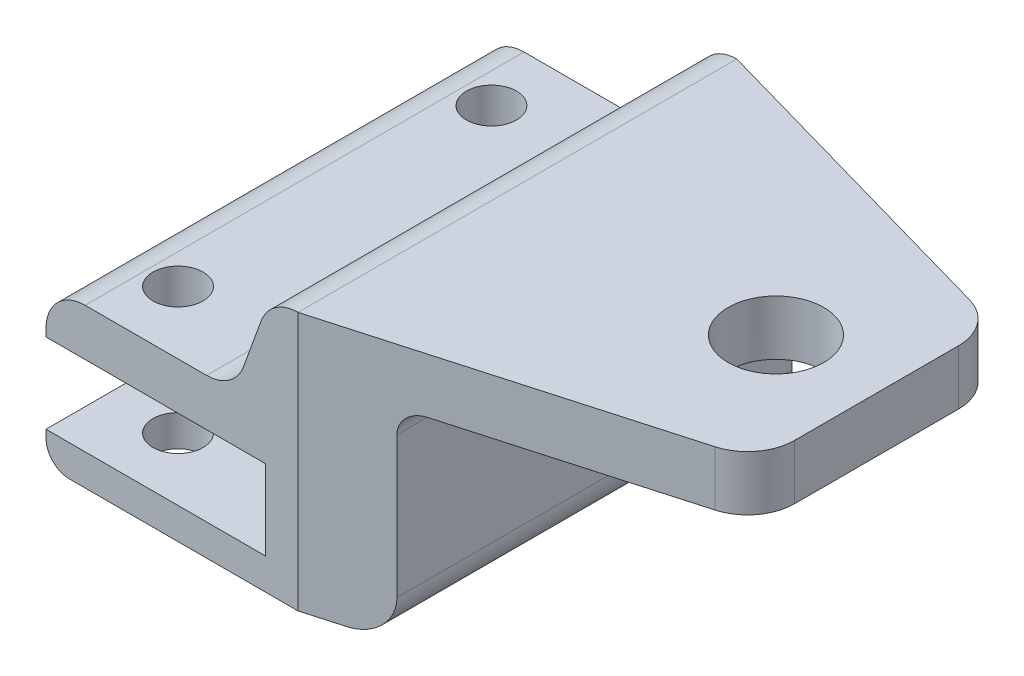
SolidWorks part; units mm, degrees
ref_plane "Plan de face" through (0, 0, 0) normal (0, 0, 1) x (1, 0, 0)
ref_plane "Plan de dessus" through (0, 0, 0) normal (0, 1, 0) x (1, 0, 0)
ref_plane "Plan de droite" through (0, 0, 0) normal (1, 0, 0) x (0, 0, -1)
sketch "Esquisse1" plane through (0, 0, 0) normal (0, 0, 1) x (1, 0, 0)
  line L0 (1.5, 0) -> (18.5, 0)
  line L1 (13.7307, 14.8551) -> (12.5987, 11.7449)
  line L2 (10.2495, 10.1) -> (2.5, 10.1)
  line L3 (0, 7.6) -> (0, 7.1)
  line L4 (0, 7.1) -> (14, 7.1)
  line L5 (14, 7.1) -> (14, 2)
  line L6 (14, 2) -> (0, 2)
  line L7 (0, 2) -> (0, 1.5)
  line L8 (16.0799, 16.5) -> (43, 16.5)
  line L9 (43, 16.5) -> (43, 13)
  line L10 (43, 13) -> (22.5, 13)
  line L11 (21, 11.5) -> (21, 2.5)
  arc A0 (21, 2.5) -> (18.5, 0) centre (18.5, 2.5) cw
  arc A1 (12.5987, 11.7449) -> (10.2495, 10.1) centre (10.2495, 12.6) cw
  arc A2 (13.7307, 14.8551) -> (16.0799, 16.5) centre (16.0799, 14) cw
  arc A3 (2.5, 10.1) -> (0, 7.6) centre (2.5, 7.6) ccw
  arc A4 (1.5, 0) -> (0, 1.5) centre (1.5, 1.5) cw
  arc A5 (22.5, 13) -> (21, 11.5) centre (22.5, 11.5) ccw
  point P17 (12, 10.1)
  point P24 (0, 0)
  point P27 (21, 13)
  dimension "D6" = 2.5
  dimension "D7" = 2.5
  dimension "D8" = 2.5
  dimension "D9" = 2.5
  dimension "D10" = 1.5
  dimension "D13" = 1.5
  dimension "D1" = 14
  dimension "D2" = 2
  dimension "D3" = 2
  dimension "D4" = 5.1
  dimension "D5" = 13
  dimension "D11" = 22
  dimension "D12" = 3.5
  dimension "D14" = 110
  dimension "D15" = 3
  dimension "D16" = 7
extrude "Boss.-Extru.1" add sketch "Esquisse1" along normal blind 28
sketch "Esquisse2" plane through (0, 10.1, 0) normal (0, 1, 0) x (1, 0, 0)
  line L0 (4.4241, -4) -> (4.4241, -24) construction
  line L1 (10.2495, -28) -> (12.5987, -28) construction
  line L3 (2.5, -28) -> (2.5, 0) construction
  line L4 (2.5, -14) -> (6.3482, -14) construction
  circle A0 centre (4.4241, -4) radius 1.6
  circle A1 centre (4.4241, -24) radius 1.6
  point P4 (4.4241, -14)
  point P5 (11.4241, -28)
  dimension "D1" = 3.2
  dimension "D2" = 3.2
  dimension "D3" = 20
  dimension "D4" = 7
extrude "Enlèv. mat.-Extru.1" cut sketch "Esquisse2" against normal through all
sketch "Esquisse3" plane through (0, 16.5, 0) normal (0, 1, 0) x (1, 0, 0)
  line L0 (16.0799, -28) -> (16.0799, 0) construction
  line L1 (32.5799, -14) -> (43, -14) construction
  line L2 (43, -28) -> (43, 0) construction
  line L4 (16.0799, -28) -> (43, -28)
  line L5 (43, -28) -> (43, 0)
  line L6 (43, 0) -> (16.0799, 0)
  line L7 (16.0799, 0) -> (36.8185, -5.8813)
  line L8 (39, -8.7675) -> (39, -19.2325)
  line L9 (36.8185, -22.1187) -> (16.0799, -28)
  circle A0 centre (32.5799, -14) radius 3.05
  arc A1 (36.8185, -5.8813) -> (39, -8.7675) centre (36, -8.7675) cw
  arc A2 (39, -19.2325) -> (36.8185, -22.1187) centre (36, -19.2325) cw
  point P20 (39, -6.5)
  point P23 (39, -21.5)
  dimension "D1" = 6.1
  dimension "D4" = 3
  dimension "D2" = 15
  dimension "D3" = 4
  dimension "D5" = 16.5
extrude "Enlèv. mat.-Extru.2" cut sketch "Esquisse3" against normal through all
